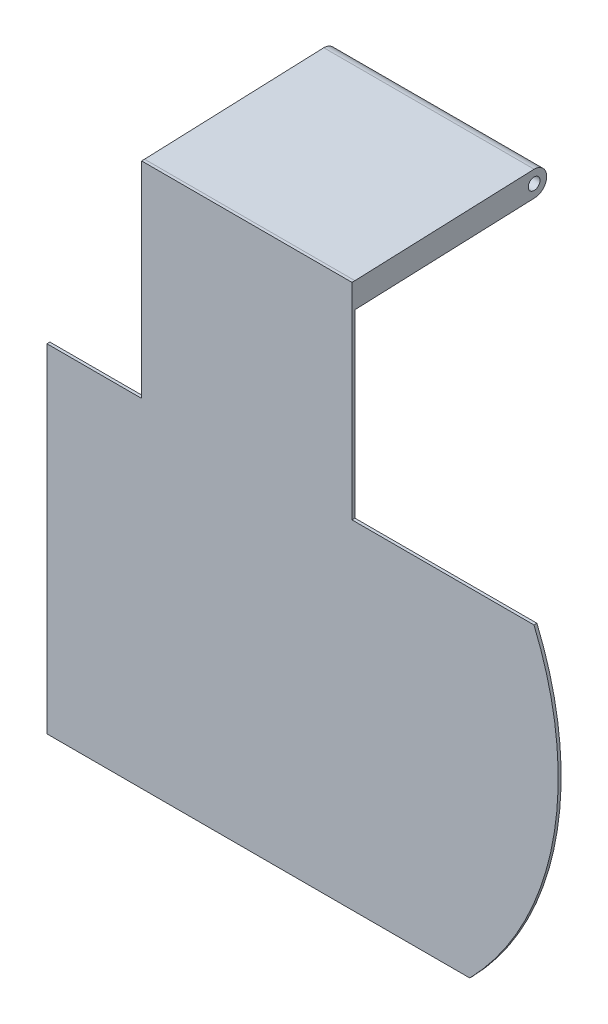
SolidWorks part; units mm, degrees
ref_plane "Piano frontale" through (0, 0, 0) normal (0, 0, 1) x (1, 0, 0)
ref_plane "Piano superiore" through (0, 0, 0) normal (0, 1, 0) x (1, 0, 0)
ref_plane "Piano destro" through (0, 0, 0) normal (1, 0, 0) x (0, 0, -1)
sketch "Schizzo1" plane through (0, 0, 0) normal (0, 0, 1) x (-1, 0, 0)
  line L0 (0, 106) -> (0, 74) construction
  line L2 (106, 0) -> (68, 0) construction
  line L3 (0, 74) -> (68, 74) construction
  line L4 (68, 74) -> (68, -41)
  line L5 (68, -41) -> (-97.7497, -41)
  line L6 (68, 74) -> (-75.8947, 74)
  line L8 (32.3, -100.959) -> (32.3, -50.959)
  line L10 (32.3, -50.959) -> (-32.3, -50.959)
  line L12 (-32.3, -50.959) -> (-32.3, -100.959)
  arc A2 (32.3, -100.959) -> (-32.3, -100.959) centre (0, 0) ccw
extrude "Estrusione-Estrusione1" add sketch "Schizzo1" along normal blind 1 contours L6 A2 L5 L4
sketch "Schizzo2" plane through (0, 0, 0) normal (0, 0, -1) x (-1, 0, 0)
  line L0 (-14.8748, 41) -> (-35.8048, 41) construction
  line L1 (68, 41) -> (-97.7497, 41) construction
  line L2 (-35.8048, 41) -> (-35.8048, 111)
  line L3 (-35.8048, 111) -> (35.7952, 111)
  line L4 (35.7952, 111) -> (35.7952, 41)
  line L5 (35.7952, 41) -> (-35.8048, 41)
extrude "Estrusione-Estrusione2" add sketch "Schizzo2" against normal blind 1 contours L5 L2 L3 L4
sketch "Schizzo3" plane through (-35.7952, 0, 0) normal (-1, 0, 0) x (0, 0, 1)
  line L0 (0, 41) -> (0, 109.07) construction
  line L1 (0, -106) -> (0, 100.959) construction
  line L2 (0, 109.07) -> (-61, 109.07) construction
  line L3 (-61, 113.3591) -> (0, 111)
  line L4 (-61, 104.7809) -> (0, 102.4217)
  line L5 (0, 102.4217) -> (0, 111)
  circle A0 centre (-61, 109.07) radius 2
  arc A1 (-61, 104.7809) -> (-61, 113.3591) centre (-61, 109.07) cw
extrude "Estrusione-Estrusione3" add sketch "Schizzo3" against normal up to surface (71.6 mm away) up to face at (35.8048, 76, 0.5)
